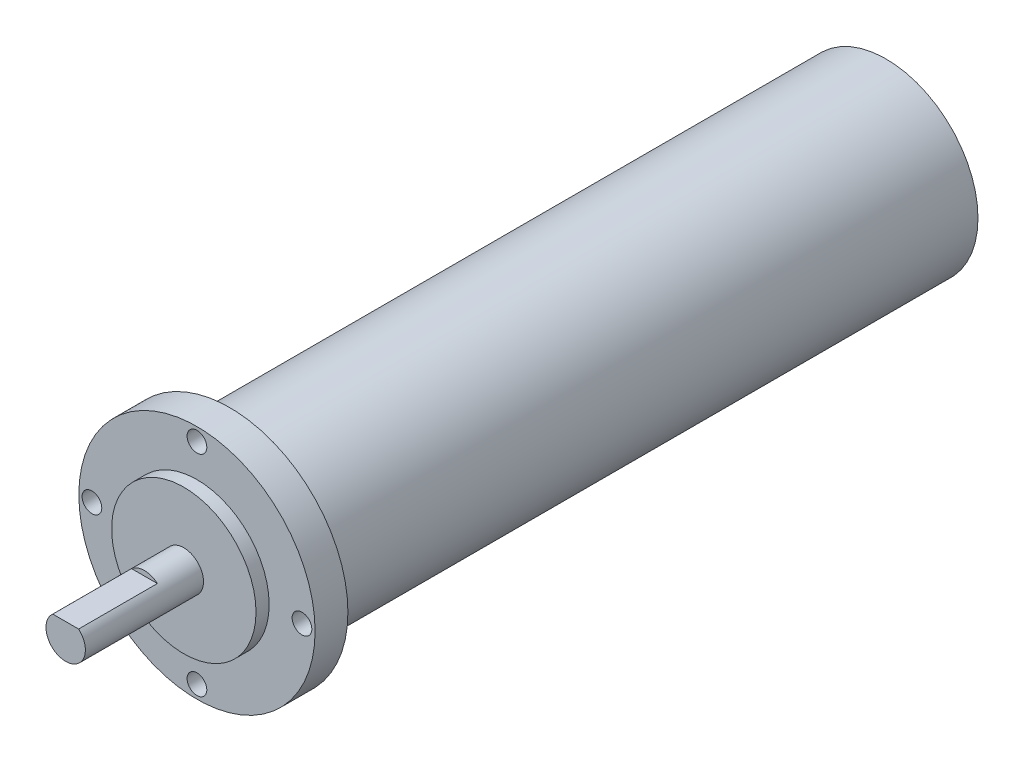
SolidWorks part; units mm, degrees
ref_plane "Front Plane" through (0, 0, 0) normal (0, 0, 1) x (1, 0, 0)
ref_plane "Top Plane" through (0, 0, 0) normal (0, 1, 0) x (1, 0, 0)
ref_plane "Right Plane" through (0, 0, 0) normal (1, 0, 0) x (0, 0, -1)
ref_plane "Plane1" through (0, 0, 0) normal (0, 0, 1) x (1, 0, 0)
ref_plane "Plane2" through (0, 0, 0) normal (0, 1, 0) x (1, 0, 0)
ref_plane "Plane3" through (0, 0, 0) normal (1, 0, 0) x (0, 0, -1)
sketch "Sketch1" plane through (0, 0, 0) normal (0, 0, 1) x (1, 0, 0)
  circle A0 centre (0, 0) radius 14
  dimension "D1" = 28
extrude "Boss-Extrude1" add sketch "Sketch1" along normal blind 100
ref_plane "Plane4" through (0, 0, 100) normal (0, 0, 1) x (1, 0, 0)
sketch "Sketch3" plane through (0, 0, 100) normal (0, 0, 1) x (1, 0, 0)
  circle A0 centre (0, 0) radius 18
  circle A1 centre (0, 0) radius 16 construction
  circle A2 centre (16, 0) radius 1.5
  circle A3 centre (0, 16) radius 1.5
  circle A4 centre (-16, 0) radius 1.5
  circle A5 centre (0, -16) radius 1.5
  dimension "D1" = 36
  dimension "D2" = 32
  dimension "D3" = 3
extrude "Boss-Extrude2" add sketch "Sketch3" along normal blind 5
ref_plane "Plane5" through (0, 0, 105) normal (0, 0, 1) x (1, 0, 0)
sketch "Sketch4" plane through (0, 0, 105) normal (0, 0, 1) x (1, 0, 0)
  circle A0 centre (0, 0) radius 11
  dimension "D1" = 22
extrude "Boss-Extrude3" add sketch "Sketch4" along normal blind 2 separate body
ref_plane "Plane6" through (0, 0, 107) normal (0, 0, 1) x (1, 0, 0)
sketch "Sketch5" plane through (0, 0, 107) normal (0, 0, 1) x (1, 0, 0)
  circle A0 centre (0, 0) radius 3
  dimension "D1" = 6
extrude "Boss-Extrude4" add sketch "Sketch5" along normal blind 6
sketch "Sketch7" plane through (0, 0, 107) normal (0, 0, 1) x (1, 0, 0)
  line L0 (-1.9699, 2.2627) -> (1.9699, 2.2627)
  arc A0 (-3, 0) -> (3, 0) centre (0, 0) ccw
  circle A1 centre (0, 0) radius 3 construction
  circle A2 centre (0, 0) radius 3 construction
  arc A3 (-3, 0) -> (-1.9699, 2.2627) centre (0, 0) cw
  arc A4 (3, 0) -> (1.9699, 2.2627) centre (0, 0) ccw
extrude "Boss-Extrude5" add sketch "Sketch7" along normal blind 18
